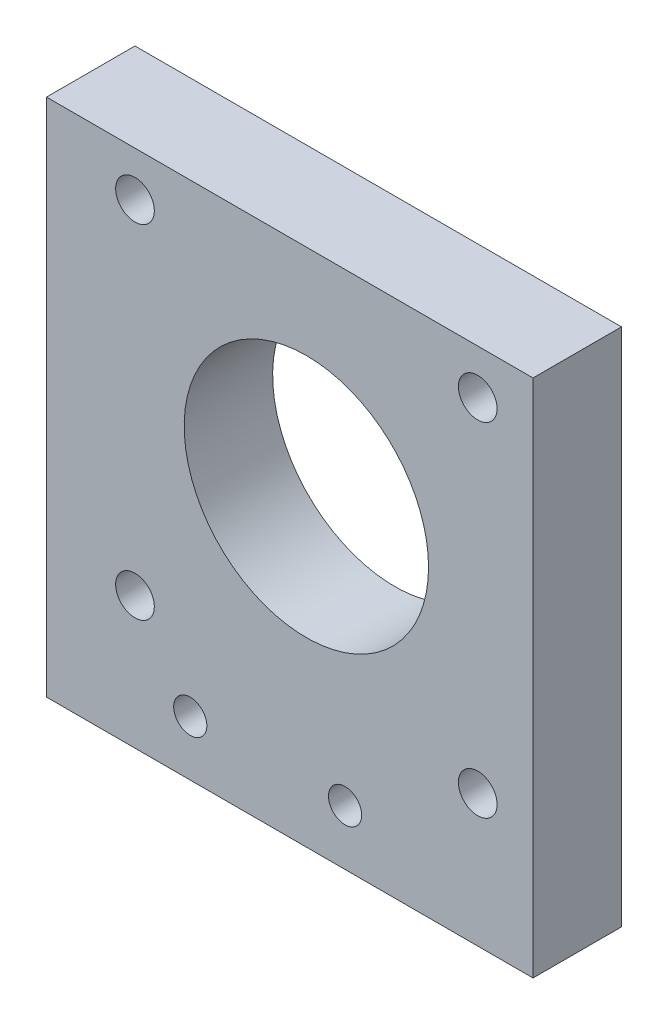
SolidWorks part; units mm, degrees
ref_plane "前视基准面" through (0, 0, 0) normal (0, 0, 1) x (1, 0, 0)
ref_plane "上视基准面" through (0, 0, 0) normal (0, 1, 0) x (1, 0, 0)
ref_plane "右视基准面" through (0, 0, 0) normal (1, 0, 0) x (0, 0, -1)
sketch "草图1" plane through (0, 0, 0) normal (1, 0, 0) x (0, 0, -1)
  line L4 (-4.5735, -8.3) -> (-4.5735, 38.7)
  line L5 (-4.5735, 38.7) -> (3.4265, 38.7)
  line L6 (3.4265, 38.7) -> (3.4265, -8.3)
  line L7 (-4.5735, -8.3) -> (3.4265, -8.3)
  dimension "D4" = 47
  dimension "D5" = 8
extrude "凸台-拉伸1" add sketch "草图1" against normal blind 44
sketch "草图2" plane through (0, 0, -3.4265) normal (0, 0, -1) x (-1, 0, 0)
  line L0 (44, -8.3) -> (0, -8.3) construction
  line L1 (20.5, 19.1591) -> (0, 19.1591) construction
  line L2 (20.5, 19.1591) -> (5, 19.1591) construction
  line L3 (5, 19.1591) -> (5, 34.6591) construction
  line L4 (5, 19.1591) -> (5, 3.6591) construction
  line L5 (20.5, 19.1591) -> (36, 19.1591) construction
  line L6 (36, 19.1591) -> (36, 34.6591) construction
  line L7 (36, 19.1591) -> (36, 3.6591) construction
  line L8 (22, -3.3) -> (17, -3.3) construction
  line L9 (22, -3.3) -> (31, -3.3) construction
  line L10 (22, -3.3) -> (22, -8.3) construction
  line L11 (44, 38.7) -> (0, 38.7) construction
  line L13 (0, -8.3) -> (0, 38.7) construction
  circle A0 centre (20.5, 19.1591) radius 11.05
  circle A1 centre (5, 34.6591) radius 1.75
  circle A2 centre (5, 3.6591) radius 1.75
  circle A3 centre (36, 3.6591) radius 1.75
  circle A4 centre (36, 34.6591) radius 1.75
  circle A5 centre (17, -3.3) radius 1.5
  circle A6 centre (31, -3.3) radius 1.5
  dimension "D4" = 22.1
  dimension "D5" = 3.5
  dimension "D6" = 3.5
  dimension "D7" = 3.5
  dimension "D8" = 3.5
  dimension "D12" = 3
  dimension "D13" = 3
  dimension "D1" = 27.5
  dimension "D2" = 15.5
  dimension "D3" = 15.5
  dimension "D9" = 9
  dimension "D10" = 5
  dimension "D11" = 5
  dimension "D14" = 19.5409
  dimension "D15" = 20.5
extrude "切除-拉伸1" cut sketch "草图2" against normal up to next
sketch "草图6" plane through (0, 0, -3.4265) normal (0, 0, -1) x (-1, 0, 0)
  line L0 (22, -8.3) -> (22, -3.3) construction
  line L1 (44, -8.3) -> (0, -8.3) construction
  line L2 (22, -3.3) -> (17, -3.3) construction
  line L3 (22, -3.3) -> (31, -3.3) construction
  circle A0 centre (17, -3.3) radius 3
  circle A1 centre (31, -3.3) radius 3
  dimension "D4" = 6
  dimension "D5" = 6
  dimension "D1" = 9
  dimension "D2" = 5
  dimension "D3" = 5
extrude "切除-拉伸3" cut sketch "草图6" against normal blind 4
